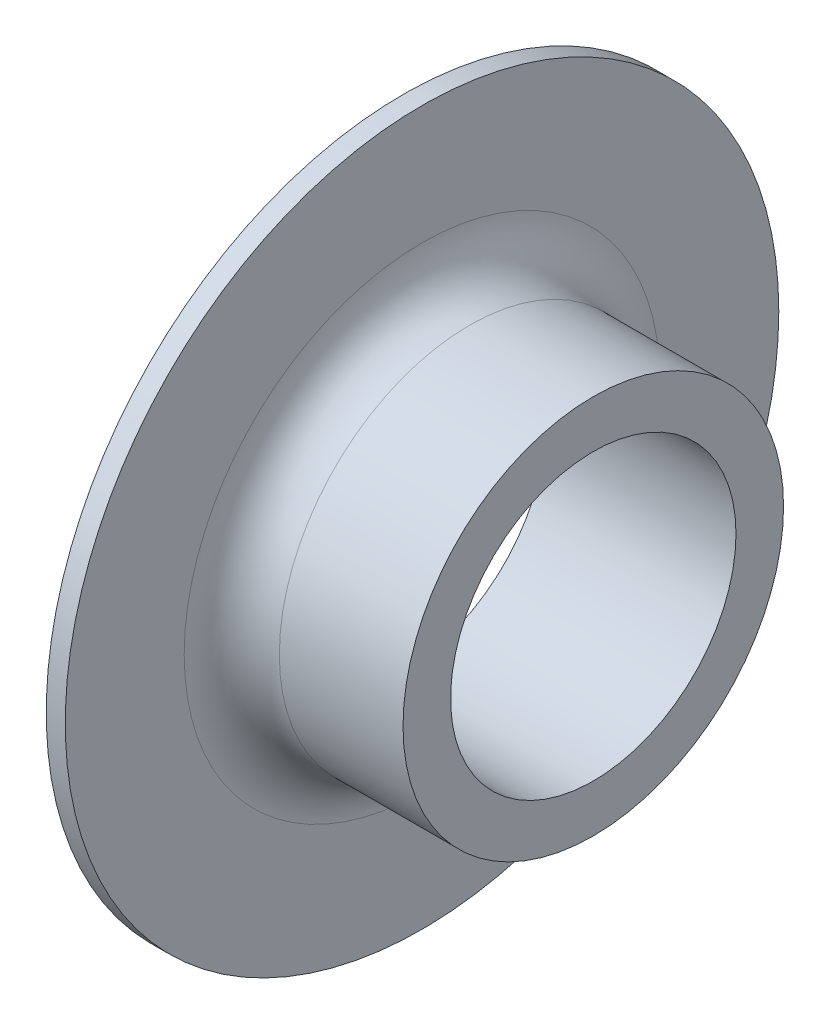
SolidWorks part; units mm, degrees
ref_plane "Ön Düzlem" through (0, 0, 0) normal (0, 0, 1) x (1, 0, 0)
ref_plane "Üst Düzlem" through (0, 0, 0) normal (0, 1, 0) x (1, 0, 0)
ref_plane "Sağ Düzlem" through (0, 0, 0) normal (1, 0, 0) x (0, 0, -1)
sketch "Sketch2" plane through (0, 0, 0) normal (0, 0, 1) x (1, 0, 0)
  line L0 (13.9591, 37.5) -> (15.9591, 37.5)
  line L1 (15.9591, 37.5) -> (15.9591, 20)
  line L2 (15.9591, 20) -> (33.9591, 20)
  line L3 (33.9591, 20) -> (33.9591, 15)
  line L4 (33.9591, 15) -> (13.9591, 15)
  line L5 (13.9591, 15) -> (13.9591, 37.5)
  line L6 (66.8659, 0) -> (0, 0) construction
  dimension "D1" = 15
  dimension "D2" = 20
  dimension "D3" = 5
  dimension "D4" = 2
  dimension "D5" = 37.5
revolve "Revolve1" add sketch "Sketch2" angle 360 about L6
fillet "Fillet1" radius 5 1 edges at (15.9591, 0, -20)
